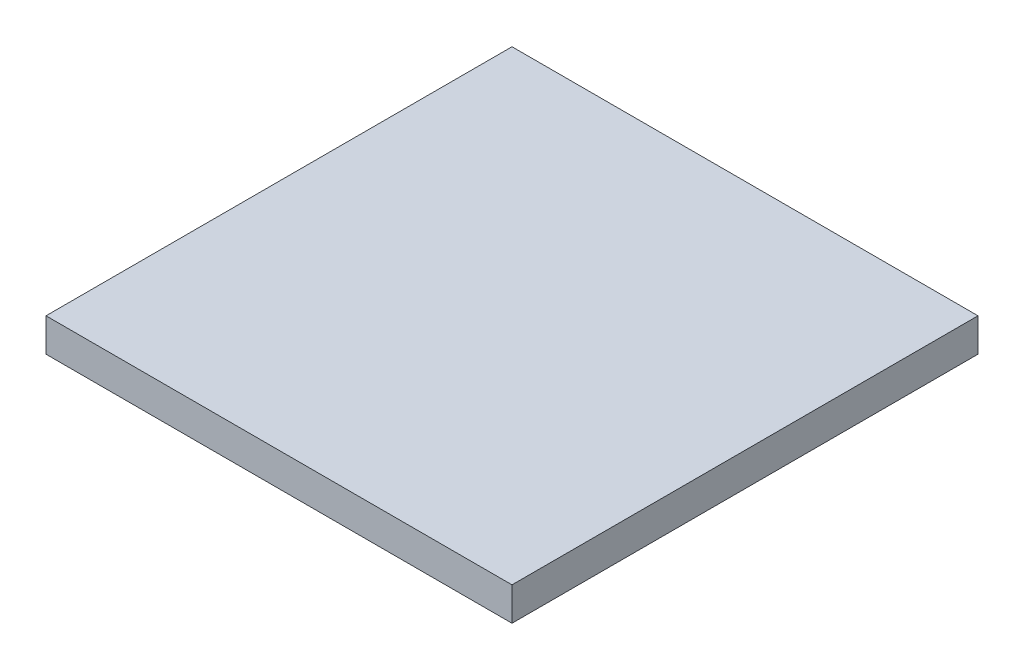
SolidWorks part; units mm, degrees
material "玻璃"
ref_plane "前视基准面" through (0, 0, 0) normal (0, 0, 1) x (1, 0, 0)
ref_plane "上视基准面" through (0, 0, 0) normal (0, 1, 0) x (1, 0, 0)
ref_plane "右视基准面" through (0, 0, 0) normal (1, 0, 0) x (0, 0, -1)
sketch "草图1" plane through (0, 0, 0) normal (0, 1, 0) x (1, 0, 0)
  line L1 (-2.1, 2.1) -> (2.1, 2.1)
  line L2 (-2.1, 2.1) -> (-2.1, -2.1)
  line L3 (-2.1, -2.1) -> (2.1, -2.1)
  line L4 (2.1, 2.1) -> (2.1, -2.1)
  line L5 (-2.1, 2.1) -> (2.1, -2.1) construction
  line L6 (-2.1, -2.1) -> (2.1, 2.1) construction
  point P0 (0, 0)
  point P6 (-2.1, 0)
  dimension "D1" = 2.1
  dimension "D2" = 4.2
extrude "凸台-拉伸1" add sketch "草图1" along normal blind 0.3
